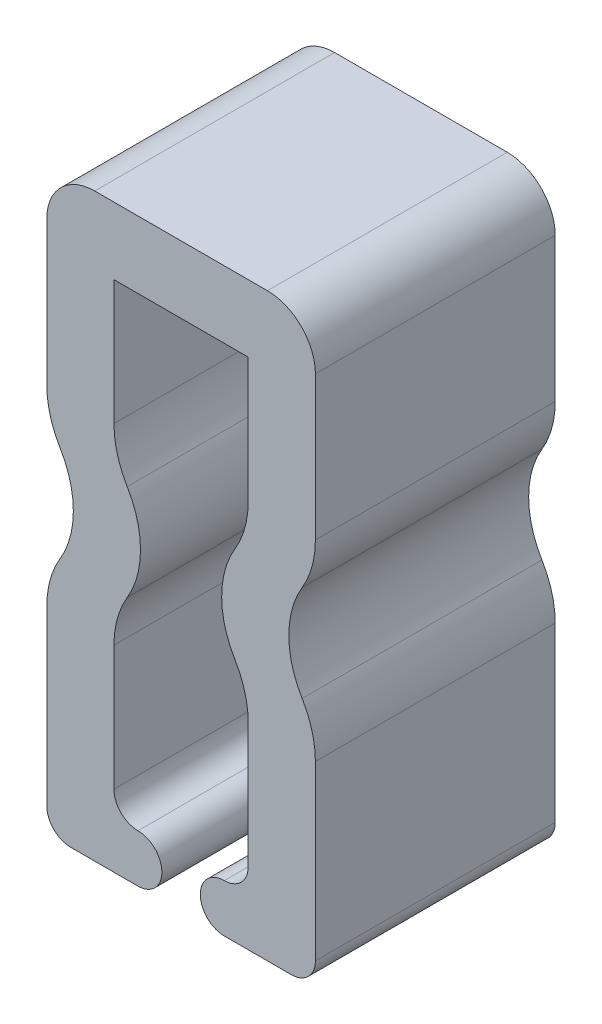
SolidWorks part; units mm, degrees
ref_plane "Front Plane" through (0, 0, 0) normal (0, 0, 1) x (1, 0, 0)
ref_plane "Top Plane" through (0, 0, 0) normal (0, 1, 0) x (1, 0, 0)
ref_plane "Right Plane" through (0, 0, 0) normal (1, 0, 0) x (0, 0, -1)
sketch "DualPropShadow" plane through (0, 0, 0) normal (0, 0, 1) x (1, 0, 0)
  line L0 (-1.2, 1.2) -> (0, 3.2)
  line L1 (-1.2, -1.2) -> (1.2, -1.2)
  line L2 (-1.2, -1.2) -> (-1.2, 1.2)
  line L3 (-1.2, 1.2) -> (1.2, 1.2) construction
  line L4 (1.2, -1.2) -> (1.2, 1.2)
  line L5 (-1.2, -1.2) -> (1.2, 1.2) construction
  line L6 (-1.2, 1.2) -> (1.2, -1.2) construction
  line L7 (0, 3.2) -> (1.2, 1.2)
  line L8 (0, 5.2) -> (0, 1.2) construction
  line L9 (-1000, 3.2) -> (49000, 3.2) construction
  line L10 (-1.2, 5.2) -> (1.2, 7.6) construction
  line L11 (-1.2, 7.6) -> (1.2, 5.2) construction
  line L12 (-1.2, 5.2) -> (1.2, 5.2) construction
  line L13 (0, 3.2) -> (1.2, 5.2)
  line L14 (1.2, 7.6) -> (1.2, 5.2)
  line L15 (-1.2, 7.6) -> (-1.2, 5.2)
  line L16 (-1.2, 7.6) -> (1.2, 7.6)
  line L17 (-1.2, 5.2) -> (0, 3.2)
  point P0 (0, 0)
  point P6 (1.2, 0)
  point P16 (0, 6.4)
  dimension "D1" = 2.4
  dimension "D2" = 4.4
  dimension "D3" = 2.4
sketch "Sketch2" plane through (0, 0, 0) normal (0, 0, 1) x (1, 0, 0)
  line L0 (-1.2, -1.2) -> (-1.2, 1.2) construction
  line L1 (-1.2, -1.2) -> (1.2, -1.2) construction
  line L2 (1.2, -1.2) -> (1.2, 1.2) construction
  line L3 (0, 3.2) -> (1.2, 1.2) construction
  line L4 (-1.2, 1.2) -> (0, 3.2) construction
  line L5 (1.2, 7.6) -> (1.2, 5.2) construction
  line L6 (0, 3.2) -> (1.2, 5.2) construction
  line L7 (-1.2, 5.2) -> (0, 3.2) construction
  line L8 (-1.2, 7.6) -> (-1.2, 5.2) construction
  line L9 (-1.2, 7.6) -> (1.2, 7.6) construction
  line L10 (-1.2, -1.2) -> (-1.2, 1.2) construction
  line L11 (-1.2, -1.2) -> (1.2, -1.2) construction
  line L12 (1.2, -1.2) -> (1.2, 1.2) construction
  line L13 (0, 3.2) -> (1.2, 1.2) construction
  line L14 (-1.2, 1.2) -> (0, 3.2) construction
  line L15 (1.2, 7.6) -> (1.2, 5.2) construction
  line L16 (0, 3.2) -> (1.2, 5.2) construction
  line L17 (-1.2, 5.2) -> (0, 3.2) construction
  line L18 (-1.2, 7.6) -> (-1.2, 5.2) construction
  line L19 (-1.2, 7.6) -> (1.2, 7.6) construction
  line L20 (0, -996.8) -> (0, 49003.2) construction
  line L21 (-1000, 3.2) -> (49000, 3.2) construction
  line L22 (-1.4, 7.8) -> (1.4, 7.8)
  line L23 (-1.2, 7.8) -> (-1.2, 7.6) construction
  line L24 (-1.4, 7.8) -> (-1.4, 5.2)
  line L25 (-1.4, -1.4) -> (-1.4, 1.2)
  line L26 (-1.2, 7.6) -> (-1.4, 7.6) construction
  line L27 (-0.846, 3.2) -> (-0.846, 4.6101) construction
  line L28 (-1.4, 5.2) -> (-1.4, 1.2) construction
  line L29 (-1.123, 4.2) -> (-0.523, 3.2) construction
  line L30 (1.8, 9.2) -> (-1.8, 9.2)
  line L31 (-1.4, 5.2) -> (-1.4, 1.2) construction
  line L32 (-1.4, -1.4) -> (1.4, -1.4) construction
  line L33 (1.4, 7.8) -> (1.4, 5.2) construction
  line L34 (-1.4, 7.8) -> (1.4, 7.8) construction
  line L35 (1.4, -1.4) -> (1.4, 1.2) construction
  line L36 (-2.8, 8.2) -> (-2.8, 5.2)
  line L37 (-1.4, 9.2) -> (-1.4, 7.8) construction
  line L38 (-1.4, 7.8) -> (-2.8, 7.8) construction
  line L39 (2.8, 8.2) -> (2.8, 5.2)
  line L40 (-0.4, -2.4) -> (-0.4, -1.2) construction
  line L41 (-1.2, 0) -> (-0.4, 0) construction
  line L42 (-0.4, 0) -> (0.4, 0) construction
  line L43 (0.4, 0) -> (1.2, 0) construction
  line L44 (-2.8, 1.2) -> (-2.8, -2.4)
  line L45 (-2.3, -2.9) -> (-0.9, -2.9)
  line L46 (1.4, 7.8) -> (1.4, 5.2)
  line L47 (1.4, 5.2) -> (1.4, 1.2) construction
  line L48 (2.3, -2.9) -> (0.9, -2.9)
  line L49 (1.4, -1.4) -> (1.4, 1.2)
  line L50 (2.8, 1.2) -> (2.8, -2.4)
  line L51 (-1.4, 8.5) -> (0, 8.5) construction
  arc A0 (-1.4, 5.2) -> (-1.123, 4.2) centre (0.5437, 5.2) ccw
  arc A1 (-1.123, 4.2) -> (-1.123, 2.2) centre (-2.7897, 3.2) cw
  arc A2 (-1.4, 1.2) -> (-1.123, 2.2) centre (0.5437, 1.2) cw
  arc A3 (-2.8, 5.2) -> (-2.523, 4.2) centre (-0.8563, 5.2) ccw
  arc A4 (-2.8, 1.2) -> (-2.523, 2.2) centre (-0.8563, 1.2) cw
  arc A5 (-2.523, 4.2) -> (-2.523, 2.2) centre (-4.1897, 3.2) cw
  arc A6 (-2.8, 8.2) -> (-1.8, 9.2) centre (-1.8, 8.2) cw
  arc A7 (-1.4, -1.4) -> (-0.9, -1.9) centre (-0.9, -1.4) ccw
  arc A8 (-0.9, -1.9) -> (-0.4, -2.4) centre (-0.9, -2.4) cw
  arc A9 (-2.8, -2.4) -> (-2.3, -2.9) centre (-2.3, -2.4) ccw
  arc A10 (-0.4, -2.4) -> (-0.9, -2.9) centre (-0.9, -2.4) cw
  arc A11 (2.8, 8.2) -> (1.8, 9.2) centre (1.8, 8.2) ccw
  arc A12 (1.4, 5.2) -> (1.123, 4.2) centre (-0.5437, 5.2) cw
  arc A13 (2.8, -2.4) -> (2.3, -2.9) centre (2.3, -2.4) cw
  arc A14 (2.8, 5.2) -> (2.523, 4.2) centre (0.8563, 5.2) cw
  arc A15 (2.8, 1.2) -> (2.523, 2.2) centre (0.8563, 1.2) ccw
  arc A16 (2.523, 4.2) -> (2.523, 2.2) centre (4.1897, 3.2) ccw
  arc A17 (1.4, 1.2) -> (1.123, 2.2) centre (-0.5437, 1.2) ccw
  arc A18 (1.123, 4.2) -> (1.123, 2.2) centre (2.7897, 3.2) ccw
  arc A19 (0.4, -2.4) -> (0.9, -2.9) centre (0.9, -2.4) ccw
  arc A20 (1.4, -1.4) -> (0.9, -1.9) centre (0.9, -1.4) cw
  arc A21 (0.9, -1.9) -> (0.4, -2.4) centre (0.9, -2.4) ccw
  point P60 (-1.2, 0)
  point P66 (0, 9.2)
  point P67 (0, 7.8)
  dimension "D3" = 1
  dimension "D4" = 0.5
  dimension "D2" = 1.4
  dimension "D1" = 0.2
extrude "Boss-Extrude1" add sketch "Sketch2" along normal blind 5
equation "\"prop_height\"= 4.4mm"
equation "\"prop_th\"= 2.4mm"
equation "\"prop_indent_height\"= 2.4mm"
equation "\"prop_radius\"= 42mm"
equation "\"D1@DualPropShadow\" = \"prop_indent_height\""
equation "\"D2@DualPropShadow\" = \"prop_height\""
equation "\"D3@DualPropShadow\" = \"prop_th\""
